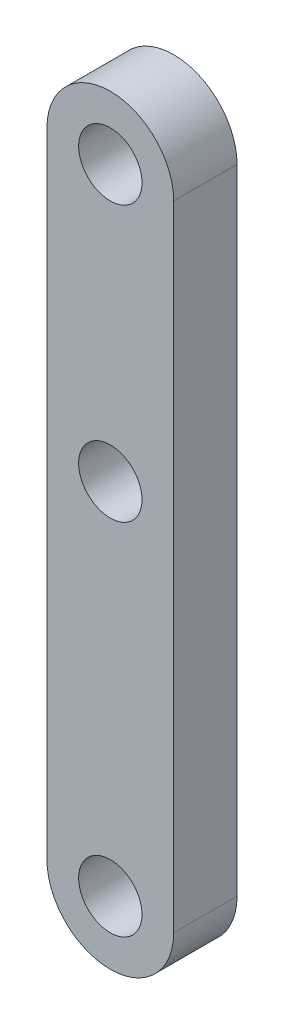
SolidWorks part; units mm, degrees
material "ﾎﾟﾘｵｷｼﾒﾁﾚﾝ(POM)ｱｾﾀｰﾙ共重合体"
ref_plane "正面" through (0, 0, 0) normal (0, 0, 1) x (1, 0, 0)
ref_plane "平面" through (0, 0, 0) normal (0, 1, 0) x (1, 0, 0)
ref_plane "右側面" through (0, 0, 0) normal (1, 0, 0) x (0, 0, -1)
sketch "ｽｹｯﾁ1" plane through (0, 0, 0) normal (0, 0, 1) x (1, 0, 0)
  line L0 (0, 0) -> (0, -30) construction
  line L1 (-3, 0) -> (-3, -30)
  line L2 (3, 0) -> (3, -30)
  line L3 (0, -15) -> (-3, -15) construction
  circle A0 centre (0, 0) radius 1.5
  arc A1 (3, 0) -> (-3, 0) centre (0, 0) ccw
  circle A2 centre (0, -30) radius 1.5
  arc A3 (3, -30) -> (-3, -30) centre (0, -30) cw
  arc A4 (0, -3) -> (3, 0) centre (0, 0) ccw construction
  arc A5 (-3, 0) -> (0, -3) centre (0, 0) ccw construction
  arc A6 (-3, -30) -> (0, -27) centre (0, -30) cw construction
  arc A7 (0, -27) -> (3, -30) centre (0, -30) cw construction
  circle A8 centre (0, -13) radius 1.5
  dimension "D1" = 3
  dimension "D2" = 6
  dimension "D5" = 3
  dimension "D3" = 6
  dimension "D4" = 30
  dimension "D6" = 13
extrude "ﾎﾞｽ - 押し出し1" add sketch "ｽｹｯﾁ1" along normal blind 3
